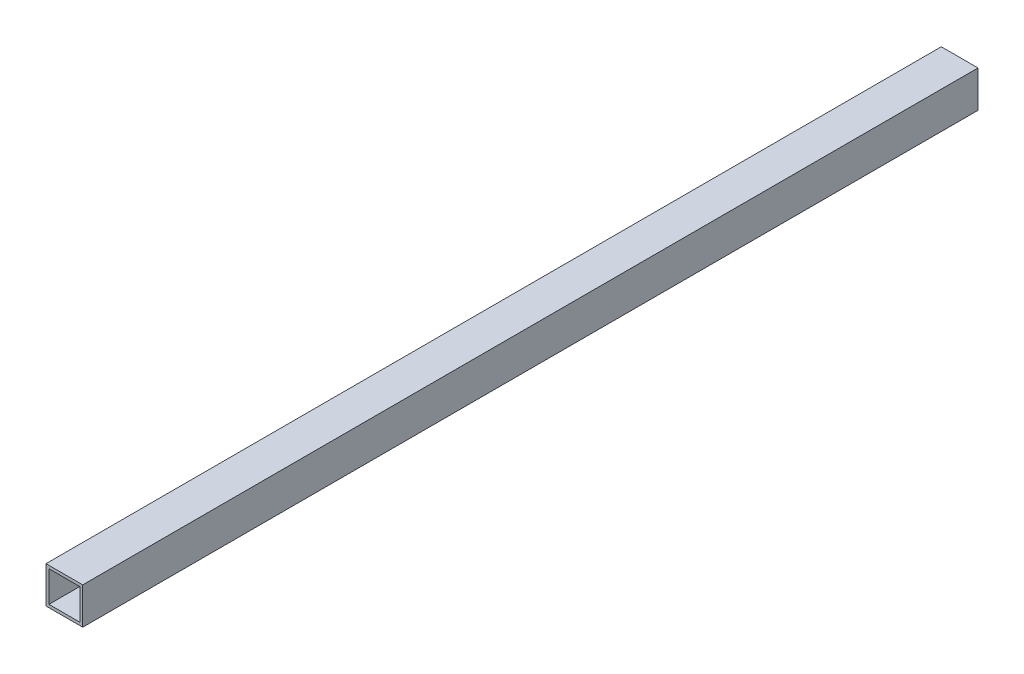
SolidWorks part; units mm, degrees
ref_plane "Front Plane" through (0, 0, 0) normal (0, 0, 1) x (1, 0, 0)
ref_plane "Top Plane" through (0, 0, 0) normal (0, 1, 0) x (1, 0, 0)
ref_plane "Right Plane" through (0, 0, 0) normal (1, 0, 0) x (0, 0, -1)
sketch "Sketch1" plane through (0, 0, 0) normal (0, 0, 1) x (1, 0, 0)
  line L0 (-10.5, -10.5) -> (-10.5, 10.5)
  line L1 (12.5, -12.5) -> (-12.5, -12.5)
  line L2 (12.5, -12.5) -> (12.5, 12.5)
  line L3 (12.5, 12.5) -> (-12.5, 12.5)
  line L4 (-12.5, -12.5) -> (-12.5, 12.5)
  line L5 (12.5, -12.5) -> (-12.5, 12.5) construction
  line L6 (12.5, 12.5) -> (-12.5, -12.5) construction
  line L7 (10.5, 10.5) -> (-10.5, 10.5)
  line L8 (10.5, -10.5) -> (10.5, 10.5)
  line L9 (10.5, -10.5) -> (-10.5, -10.5)
  point P0 (0, 0)
  dimension "Width" = 25
  dimension "Wall thk." = 2
sketch "Sketch2" plane through (0, 0, 0) normal (1, 0, 0) x (0, 0, -1)
  line L0 (-304.8, 0) -> (304.8, 0) construction
  point P0 (-292.608, 0)
  point P3 (292.608, 0)
  point P4 (0, 0)
  dimension "Length" = 609.6
  dimension "D1" = 12.192
  dimension "D2" = 12.192
sketch "Sketch3" plane through (0, 0, 0) normal (0, 0, 1) x (1, 0, 0)
  line L0 (10.5, -10.5) -> (-10.5, -10.5) construction
  line L1 (10.5, -10.5) -> (10.5, 10.5) construction
  line L2 (10.5, 10.5) -> (-10.5, 10.5) construction
  line L3 (-10.5, -10.5) -> (-10.5, 10.5) construction
  line L4 (12.5, -12.5) -> (-12.5, -12.5) construction
  line L5 (12.5, -12.5) -> (12.5, 12.5) construction
  line L6 (12.5, 12.5) -> (-12.5, 12.5) construction
  line L7 (-12.5, -12.5) -> (-12.5, 12.5) construction
  line L8 (10.5, -10.5) -> (-10.5, -10.5)
  line L9 (10.5, -10.5) -> (10.5, 10.5)
  line L10 (10.5, 10.5) -> (-10.5, 10.5)
  line L11 (-10.5, -10.5) -> (-10.5, 10.5)
  line L12 (12.5, -12.5) -> (-12.5, -12.5)
  line L13 (12.5, -12.5) -> (12.5, 12.5)
  line L14 (12.5, 12.5) -> (-12.5, 12.5)
  line L15 (-12.5, -12.5) -> (-12.5, 12.5)
extrude "Boss-Extrude1" add sketch "Sketch3" along normal up to vertex (304.8 mm away) and the other way up to vertex (304.8 mm away) up to point (0, 0, 304.8) other way up to point (0, 0, -304.8)
equation "\"D1@Sketch2\"=\"Length@Sketch2\"*.02"
equation "\"D2@Sketch2\"=\"D1@Sketch2\""
